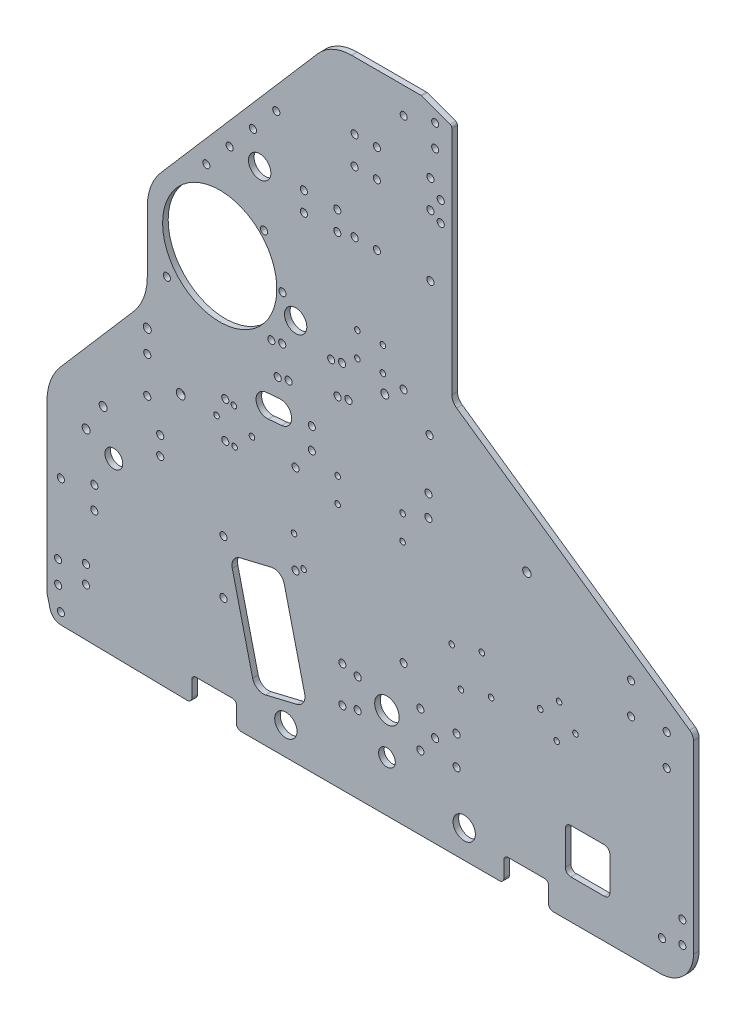
SolidWorks part; units mm, degrees
ref_plane "Front Plane" through (0, 0, 0) normal (0, 0, 1) x (1, 0, 0)
ref_plane "Top Plane" through (0, 0, 0) normal (0, 1, 0) x (1, 0, 0)
ref_plane "Right Plane" through (0, 0, 0) normal (1, 0, 0) x (0, 0, -1)
sketch "Sketch1" plane through (0, 0, 0) normal (0, 0, 1) x (1, 0, 0)
  line L0 (82.55, -20.32) -> (82.55, -6.35)
  line L2 (0, 0) -> (0, 157.48)
  line L4 (368.3, -20.32) -> (368.3, 106.68)
  line L5 (82.55, -6.35) -> (107.95, -6.35)
  line L6 (107.95, -6.35) -> (107.95, -20.32)
  line L7 (107.95, -20.32) -> (260.35, -20.32)
  line L8 (260.35, -20.32) -> (260.35, -6.35)
  line L9 (260.35, -6.35) -> (285.75, -6.35)
  line L10 (285.75, -6.35) -> (285.75, -20.32)
  line L11 (285.75, -20.32) -> (368.3, -20.32)
  line L12 (361.95, 12.7) -> (368.3, 12.7) construction
  line L13 (0, 0) -> (6.35, 0) construction
  line L14 (0.1896, -7.8901) -> (1.7771, -14.2401)
  line L15 (7.8295, -19.0491) -> (82.55, -20.32)
  line L16 (0, 0) -> (0, -6.35)
  line L17 (76.2, 128.905) -> (79.375, 128.905) construction
  line L18 (57.15, 118.5863) -> (101.6, 118.5862) construction
  line L19 (57.15, 118.5863) -> (57.15, 139.2238) construction
  line L20 (101.6, 118.5862) -> (101.6, 139.2237) construction
  line L21 (57.15, 139.2238) -> (101.6, 139.2237) construction
  line L22 (57.15, 118.5863) -> (101.6, 139.2237) construction
  line L23 (101.6, 118.5862) -> (57.15, 139.2238) construction
  line L24 (101.6, 139.2237) -> (125.4682, 147.9111) construction
  line L25 (203.2, 59.805) -> (203.2, 194.805) construction
  line L26 (203.2, 194.805) -> (203.2, 329.805) construction
  line L27 (355.6, 332.105) -> (330.2, 332.105) construction
  line L28 (330.2, 332.105) -> (330.2, 217.805) construction
  line L29 (330.2, 217.805) -> (355.6, 217.805) construction
  line L30 (355.6, 217.805) -> (355.6, 332.105) construction
  line L31 (203.2, 344.805) -> (203.2, 194.805) construction
  line L32 (50.8, 332.105) -> (76.2, 332.105) construction
  line L33 (76.2, 332.105) -> (76.2, 217.805) construction
  line L34 (50.8, 217.805) -> (50.8, 332.105) construction
  line L35 (76.2, 217.805) -> (50.8, 217.805) construction
  line L36 (213.2, 344.805) -> (230.6638, 338.455)
  line L37 (203.2, 344.805) -> (161.925, 344.805)
  line L38 (203.2, 344.805) -> (213.2, 344.805)
  line L39 (348.5362, 344.805) -> (413.4623, 344.805)
  line L40 (348.5362, 344.805) -> (230.6638, 344.805) construction
  line L42 (161.925, 344.805) -> (0, 157.48)
  line L44 (230.6638, 338.455) -> (230.6638, 202.565)
  line L45 (230.6638, 202.565) -> (368.3, 106.68)
  line L46 (213.2, 344.805) -> (-141.0713, 344.805) construction
  line L47 (350.3395, -2.3595) -> (368.3, -20.32) construction
  line L48 (125.4682, 147.9111) -> (133.0592, 148.5752) construction
  line L49 (124.9148, 154.2369) -> (132.5058, 154.901)
  line L50 (126.0216, 141.5852) -> (133.6126, 142.2494)
  circle A0 centre (6.35, 0) radius 2.032
  circle A1 centre (6.35, 12.7) radius 2.032
  circle A2 centre (361.95, 0) radius 2.032
  circle A3 centre (361.95, 12.7) radius 2.032
  arc A5 (1.7771, -14.2401) -> (7.8295, -19.0491) centre (7.9375, -12.7) ccw
  circle A6 centre (7.9375, -12.7) radius 2.032
  arc A7 (0, -6.35) -> (0.1896, -7.8901) centre (6.35, -6.35) ccw
  circle A8 centre (38.1, 78.105) radius 5.08
  circle A9 centre (76.2, 128.905) radius 2.54
  circle A10 centre (101.6, 118.5862) radius 2.032
  circle A11 centre (101.6, 139.2237) radius 2.032
  circle A12 centre (57.15, 139.2238) radius 2.032
  circle A13 centre (57.15, 118.5863) radius 2.032
  circle A15 centre (203.2, 59.805) radius 2
  circle A16 centre (203.2, 194.805) radius 2
  circle A17 centre (203.2, 329.805) radius 2
  circle A18 centre (63.5, 313.055) radius 2.032
  circle A20 centre (355.6, 332.105) radius 2.032
  circle A21 centre (330.2, 332.105) radius 2.032
  circle A22 centre (355.6, 217.805) radius 2.032
  circle A23 centre (330.2, 217.805) radius 2.032
  circle A24 centre (50.8, 332.105) radius 2.032
  circle A25 centre (76.2, 332.105) radius 2.032
  circle A26 centre (50.8, 217.805) radius 2.032
  circle A27 centre (76.2, 217.805) radius 2.032
  circle A28 centre (221.1381, 335.28) radius 2
  circle A29 centre (224.3138, 298.831) radius 2.032
  circle A30 centre (353.06, 100.7351) radius 2.032
  circle A31 centre (332.74, 115.9751) radius 2.032
  circle A32 centre (332.74, 98.1951) radius 2.032
  circle A33 centre (353.06, 82.9551) radius 2.032
  circle A34 centre (117.3562, 280.4276) radius 2.032
  circle A35 centre (104.0678, 265.0548) radius 2.032
  circle A36 centre (90.7795, 249.682) radius 2.032
  circle A38 centre (130.6445, 295.8004) radius 2.032
  circle A39 centre (68.326, 182.9237) radius 2.032
  circle A40 centre (224.3138, 287.401) radius 2.032
  circle A41 centre (125.4682, 147.9111) radius 6.35
  circle A42 centre (221.1381, 322.58) radius 2
  circle A43 centre (350.3395, -2.3595) radius 2.032
  arc A44 (124.9148, 154.2369) -> (126.0216, 141.5852) centre (125.4682, 147.9111) ccw
  arc A45 (133.6126, 142.2494) -> (132.5058, 154.901) centre (133.0592, 148.5752) ccw
  point P82 (203.2, 344.805)
  point P90 (368.3, 62.484)
  point P107 (129.2637, 148.2431)
  dimension "D6" = 4.064
  dimension "D10" = 6.35
  dimension "D11" = 4.064
  dimension "D17" = 38.1
  dimension "D27" = 4
  dimension "D31" = 4.064
  dimension "D32" = 41.275
  dimension "D36" = 4.064
  dimension "D47" = 39.624
  dimension "D48" = 4.064
  dimension "D25" = 5.08
  dimension "D26" = 4.064
  dimension "D52" = 4.064
  dimension "D65" = 4.064
  dimension "D69" = 10.16
  dimension "D72" = 12.7
  dimension "D77" = 6.35
  dimension "D2" = 127
  dimension "D3" = 13.97
  dimension "D4" = 25.4
  dimension "D5" = 152.4
  dimension "D7" = 12.7
  dimension "D8" = 6.35
  dimension "D9" = 20.32
  dimension "D12" = 12.7
  dimension "D13" = 1.5875
  dimension "D14" = 82.55
  dimension "D15" = 368.3
  dimension "D16" = 6.35
  dimension "D18" = 98.425
  dimension "D19" = 38.1
  dimension "D20" = 50.8
  dimension "D21" = 3.175
  dimension "D22" = 270
  dimension "D23" = 20.6375
  dimension "D24" = 44.45
  dimension "D28" = 135
  dimension "D29" = 12.7
  dimension "D30" = 15
  dimension "D33" = 63.5
  dimension "D34" = 27.4638
  dimension "D35" = 12.7
  dimension "D37" = 114.3
  dimension "D38" = 25.4
  dimension "D39" = 12.7
  dimension "D40" = 157.48
  dimension "D41" = 142.24
  dimension "D42" = 365.125
  dimension "D43" = 10
  dimension "D44" = 6.35
  dimension "D45" = 31.75
  dimension "D46" = 3.175
  dimension "D49" = 6.35
  dimension "D50" = 203.2
  dimension "D51" = 15.24
  dimension "D53" = 17.78
  dimension "D54" = 17.78
  dimension "D55" = 20.32
  dimension "D56" = 15.24
  dimension "D57" = 92.202
  dimension "D58" = 8.382
  dimension "D59" = 20.32
  dimension "D60" = 20.32
  dimension "D61" = 8.382
  dimension "D62" = 20.32
  dimension "D63" = 8.382
  dimension "D64" = 8.382
  dimension "D66" = 35.052
  dimension "D67" = 68.326
  dimension "D68" = 11.43
  dimension "D70" = 25.4
  dimension "D71" = 110
  dimension "D73" = 17.9381
  dimension "D74" = 12.7
  dimension "D75" = 45
  dimension "D76" = 25.4
  dimension "D78" = 165
  dimension "D79" = 7.62
extrude "Boss-Extrude1" add sketch "Sketch1" along normal blind 3.175
fillet "Fillet1" radius 2.286 4 edges at (285.75, -6.35, 1.5875) (107.95, -6.35, 1.5875) (260.35, -6.35, 1.5875) (82.55, -6.35, 1.5875)
fillet "Fillet2" radius 6.35 1 edges at (230.6638, 202.565, 1.5875)
sketch "Sketch2" plane through (0, 0, 0) normal (0, 0, -1) x (-1, 0, 0)
  circle A0 centre (-100.5528, 71.086) radius 2.032 construction
  circle A1 centre (-100.5528, 40.606) radius 2.032 construction
  circle A2 centre (-22.225, 18.2025) radius 2.032 construction
  circle A3 centre (-22.225, 8.0425) radius 2.032 construction
  circle A4 centre (-100.5528, 71.086) radius 2.032
  circle A5 centre (-100.5528, 40.606) radius 2.032
  circle A6 centre (-22.225, 18.2025) radius 2.032
  circle A7 centre (-22.225, 8.0425) radius 2.032
extrude "Cut-Extrude1" cut sketch "Sketch2" against normal through all
fillet "Fillet3" radius 1.5875 2 edges at (230.6638, 338.455, 1.5875) (213.2, 344.805, 1.5875)
sketch "Sketch3" plane through (0, 0, 3.175) normal (0, 0, 1) x (1, 0, 0)
  line L0 (132.9524, 63.2646) -> (132.7215, 64.2281) construction
  line L1 (128.3814, 66.8897) -> (110.6828, 62.6472) construction
  line L2 (114.5132, 58.4237) -> (126.8822, 61.3887) construction
  line L3 (108.0212, 58.3071) -> (108.2522, 57.3436) construction
  line L4 (131.2006, 57.703) -> (140.0164, 20.9265) construction
  line L5 (144.0993, 16.7636) -> (132.9524, 63.2646) construction
  line L6 (108.2522, 57.3436) -> (119.3991, 10.8426) construction
  line L7 (121.1509, 16.4042) -> (112.3351, 53.1807) construction
  line L8 (119.3991, 10.8426) -> (119.6301, 9.8791) construction
  line L9 (144.3303, 15.8001) -> (144.0993, 16.7636) construction
  line L10 (137.8383, 15.6835) -> (125.4694, 12.7185) construction
  line L11 (123.9701, 7.2175) -> (141.6687, 11.4601) construction
  line L12 (132.9524, 63.2646) -> (132.7215, 64.2281)
  line L13 (128.3814, 66.8897) -> (110.6828, 62.6472)
  line L14 (114.5132, 58.4237) -> (126.8822, 61.3887)
  line L15 (108.0212, 58.3071) -> (108.2522, 57.3436)
  line L16 (131.2006, 57.703) -> (140.0164, 20.9265)
  line L17 (144.0993, 16.7636) -> (132.9524, 63.2646)
  line L18 (108.2522, 57.3436) -> (119.3991, 10.8426)
  line L19 (121.1509, 16.4042) -> (112.3351, 53.1807)
  line L20 (119.3991, 10.8426) -> (119.6301, 9.8791)
  line L21 (144.3303, 15.8001) -> (144.0993, 16.7636)
  line L22 (137.8383, 15.6835) -> (125.4694, 12.7185)
  line L23 (123.9701, 7.2175) -> (141.6687, 11.4601)
  line L24 (127.7894, 69.3598) -> (110.0908, 65.1172)
  line L25 (105.5512, 57.715) -> (105.7822, 56.7515)
  line L26 (105.7822, 56.7515) -> (116.9291, 10.2505)
  line L27 (116.9291, 10.2505) -> (117.16, 9.287)
  line L28 (124.5622, 4.7475) -> (142.2608, 8.99)
  line L29 (146.8003, 16.3922) -> (146.5694, 17.3557)
  line L30 (146.5694, 17.3557) -> (135.4225, 63.8567)
  line L31 (135.4225, 63.8567) -> (135.1915, 64.8202)
  line L32 (14.605, -0.1369) -> (103.7278, 32.3011) construction
  line L33 (14.605, -0.1369) -> (103.7278, 32.3011)
  line L34 (0, -6.35) -> (0, 157.48) construction
  line L35 (-39.6666, 74.7152) -> (103.7278, 126.9065) construction
  line L36 (26.9875, 46.9531) -> (26.9875, 59.6531) construction
  line L37 (107.95, -20.32) -> (260.35, -20.32) construction
  line L38 (64.5259, 92.5258) -> (64.5259, 102.9405) construction
  line L39 (131.6538, 14.201) -> (136.0946, -4.3242) construction
  line L40 (136.0946, -4.3242) -> (237.6946, -4.3242) construction
  arc A0 (132.7215, 64.2281) -> (128.6308, 66.9403) centre (129.2206, 63.3889) ccw construction
  arc A1 (110.6828, 62.6472) -> (110.4377, 62.5791) centre (111.522, 59.1463) ccw construction
  arc A2 (128.6308, 66.9403) -> (128.3814, 66.8897) centre (129.2206, 63.3889) ccw construction
  arc A3 (110.4377, 62.5791) -> (108.0212, 58.3071) centre (111.522, 59.1463) ccw construction
  arc A4 (119.6301, 9.8791) -> (123.7207, 7.1669) centre (123.1309, 10.7183) ccw construction
  arc A5 (141.9139, 11.5281) -> (144.3303, 15.8001) centre (140.8295, 14.9609) ccw construction
  arc A6 (141.6687, 11.4601) -> (141.9139, 11.5281) centre (140.8295, 14.9609) ccw construction
  arc A7 (123.7207, 7.1669) -> (123.9701, 7.2175) centre (123.1309, 10.7183) ccw construction
  arc A8 (132.7215, 64.2281) -> (128.6308, 66.9403) centre (129.2206, 63.3889) ccw
  arc A9 (110.6828, 62.6472) -> (110.4377, 62.5791) centre (111.522, 59.1463) ccw
  arc A10 (128.6308, 66.9403) -> (128.3814, 66.8897) centre (129.2206, 63.3889) ccw
  arc A11 (110.4377, 62.5791) -> (108.0212, 58.3071) centre (111.522, 59.1463) ccw
  arc A12 (119.6301, 9.8791) -> (123.7207, 7.1669) centre (123.1309, 10.7183) ccw
  arc A13 (141.9139, 11.5281) -> (144.3303, 15.8001) centre (140.8295, 14.9609) ccw
  arc A14 (141.6687, 11.4601) -> (141.9139, 11.5281) centre (140.8295, 14.9609) ccw
  arc A15 (123.7207, 7.1669) -> (123.9701, 7.2175) centre (123.1309, 10.7183) ccw
  arc A16 (110.0908, 65.1172) -> (109.6726, 65.0012) centre (111.522, 59.1463) ccw
  arc A17 (109.6726, 65.0012) -> (105.5512, 57.715) centre (111.522, 59.1463) ccw
  arc A18 (117.16, 9.287) -> (124.1369, 4.6613) centre (123.1309, 10.7183) ccw
  arc A19 (124.1369, 4.6613) -> (124.5622, 4.7475) centre (123.1309, 10.7183) ccw
  arc A20 (142.2608, 8.99) -> (142.6789, 9.1061) centre (140.8295, 14.9609) ccw
  arc A21 (142.6789, 9.1061) -> (146.8003, 16.3922) centre (140.8295, 14.9609) ccw
  arc A22 (135.1915, 64.8202) -> (128.2147, 69.446) centre (129.2206, 63.3889) ccw
  arc A23 (128.2147, 69.446) -> (127.7894, 69.3598) centre (129.2206, 63.3889) ccw
  circle A24 centre (136.0946, -4.3242) radius 6.35
  circle A25 centre (237.6946, -4.3242) radius 6.35
  circle A26 centre (134.1438, 208.2281) radius 2.032 construction
  circle A33 centre (26.9875, 46.9531) radius 2.032
  circle A34 centre (26.9875, 59.6531) radius 2.032
  circle A35 centre (7.9375, 53.3031) radius 2.032
  circle A37 centre (32.0306, 100.8109) radius 32.385 construction
  circle A38 centre (32.0306, 100.8109) radius 2.286
  circle A39 centre (123.682, 233.4851) radius 2.032 construction
  circle A40 centre (64.5259, 102.9405) radius 2.032
  circle A41 centre (64.5259, 92.5258) radius 2.032
  circle A42 centre (134.1438, 208.2281) radius 2.032
  circle A43 centre (123.682, 233.4851) radius 2.032
  ellipse E0 centre (124.5974, 48.8487) end of major axis (128.5376, 61.3578) minor radius 6 (131.2006, 57.703) -> (126.8822, 61.3887) ccw construction
  ellipse E1 centre (122.2349, 48.2824) end of major axis (113.0518, 57.6456) minor radius 6 (114.5132, 58.4237) -> (112.3351, 53.1807) ccw construction
  ellipse E2 centre (127.7541, 25.2585) end of major axis (131.6942, 37.7675) minor radius 6 (121.1509, 16.4042) -> (125.4694, 12.7185) ccw construction
  ellipse E3 centre (130.1166, 25.8248) end of major axis (139.2998, 16.4616) minor radius 6 (137.8383, 15.6835) -> (140.0164, 20.9265) ccw construction
  ellipse E4 centre (124.5974, 48.8487) end of major axis (120.6573, 36.3397) minor radius 6 (131.2006, 57.703) -> (126.8822, 61.3887) ccw
  ellipse E5 centre (122.2349, 48.2824) end of major axis (131.4181, 38.9192) minor radius 6 (114.5132, 58.4237) -> (112.3351, 53.1807) ccw
  ellipse E6 centre (127.7541, 25.2585) end of major axis (131.6942, 37.7675) minor radius 6 (121.1509, 16.4042) -> (125.4694, 12.7185) ccw
  ellipse E7 centre (130.1166, 25.8248) end of major axis (139.2998, 16.4616) minor radius 6 (137.8383, 15.6835) -> (140.0164, 20.9265) ccw
  point P93 (26.9875, 53.3031)
  point P115 (32.0306, 100.8109)
  dimension "D3" = 64.77
  dimension "D4" = 4.572
  dimension "D8" = 4.064
  dimension "D13" = 12.7
  dimension "D15" = 101.6
  dimension "D2" = 88.9
  dimension "D5" = 7.9375
  dimension "D6" = 19.05
  dimension "D7" = 73.6231
  dimension "D9" = 12.7
  dimension "D10" = 10.4147
  dimension "D11" = 37.5384
  dimension "D12" = 45.5727
  dimension "D14" = 19.05
  dimension "D1" = 2.54
extrude "Cut-Extrude2" cut sketch "Sketch3" against normal through all contours A22 A23 L24 A16 A17 L25 L26 L27 A18 A19 L28 A20 A21 L29 L30 L31 A15 A12 L20 L18 L15 A11 A9 L13 A10 A8 L12 L17 L21 A13 A14 L23 | A12 A15 L23 A14 A13 L21 L17 L12 A8 A10 L13 A9 A11 L15 L18 L20 E7 L22 E6 L19 E5 L14 E4 L16 | L22 E7 L16 E4 L14 E5 L19 E6 | A38 | A41 | A40 | A35 | A34 | A33 | A43 | A42 | A24 | A25
sketch "Sketch4" plane through (0, 0, 3.175) normal (0, 0, 1) x (1, 0, 0)
  line L0 (57.15, 139.2238) -> (101.6, 139.2237) construction
  line L1 (168.275, 21.4312) -> (212.725, 21.4312) construction
  line L2 (168.275, 21.4312) -> (168.275, 42.0687) construction
  line L3 (168.275, 42.0687) -> (212.725, 42.0687) construction
  line L4 (212.725, 21.4312) -> (212.725, 42.0687) construction
  line L5 (168.275, 21.4312) -> (212.725, 42.0687) construction
  line L6 (168.275, 42.0687) -> (212.725, 21.4312) construction
  line L7 (57.15, 118.5863) -> (57.15, 139.2238) construction
  line L8 (107.95, -20.32) -> (260.35, -20.32) construction
  line L9 (193.675, 31.75) -> (177.005, 31.75) construction
  line L10 (190.5, 31.75) -> (193.675, 31.75) construction
  line L11 (6.35, 12.7) -> (361.95, 12.7) construction
  line L12 (107.95, -6.35) -> (107.95, -20.32) construction
  line L13 (193.675, 31.75) -> (220.6625, 31.75) construction
  line L14 (177.005, 23.4569) -> (177.005, 40.0431) construction
  line L15 (213.2, 44.805) -> (193.2, 44.805) construction
  line L16 (213.2, 44.805) -> (213.2, 344.805) construction
  line L17 (213.2, 344.805) -> (193.2, 344.805) construction
  line L18 (193.2, 44.805) -> (193.2, 344.805) construction
  line L19 (213.2, 44.805) -> (193.2, 344.805) construction
  line L20 (213.2, 344.805) -> (193.2, 44.805) construction
  line L21 (226.1381, 335.28) -> (226.1381, 31.75) construction
  line L22 (237.33, 40.0431) -> (233.3612, 40.0431) construction
  line L23 (237.33, 23.4569) -> (233.3612, 23.4569) construction
  circle A0 centre (168.275, 42.0687) radius 2.032
  circle A1 centre (212.725, 42.0687) radius 2.032
  circle A2 centre (212.725, 21.4312) radius 2.032
  circle A3 centre (168.275, 21.4312) radius 2.032
  circle A4 centre (193.675, 31.75) radius 6.985
  circle A7 centre (220.6625, 31.75) radius 14.2875 construction
  circle A8 centre (193.675, 31.75) radius 12.7 construction
  circle A9 centre (177.005, 40.0431) radius 2.032
  circle A10 centre (177.005, 23.4569) radius 2.032
  circle A11 centre (237.33, 40.0431) radius 2.032 construction
  circle A12 centre (237.33, 23.4569) radius 2.032 construction
  circle A13 centre (193.675, 8.4667) radius 4.7625
  circle A14 centre (221.1381, 31.75) radius 2.032
  circle A15 centre (221.1381, 31.75) radius 5 construction
  circle A16 centre (221.1381, 335.28) radius 5 construction
  circle A17 centre (233.3612, 23.4569) radius 2.032
  circle A18 centre (233.3612, 40.0431) radius 2.032
  point P0 (190.5, 31.75)
  point P26 (203.2, 194.805)
  point P38 (177.005, 31.75)
  dimension "D1" = 4.064
  dimension "D4" = 13.97
  dimension "D7" = 9.525
  dimension "D10" = 25.4
  dimension "D11" = 28.575
  dimension "D16" = 10
  dimension "D17" = 4.064
  dimension "D18" = 10
  dimension "D2" = 52.07
  dimension "D3" = 3.175
  dimension "D5" = 82.55
  dimension "D6" = 26.9875
  dimension "D8" = 20
  dimension "D9" = 300
  dimension "D12" = 16.67
  dimension "D13" = 16.5862
  dimension "D14" = 60.325
  dimension "D15" = 23.2833
  dimension "D19" = 3.9688
extrude "Cut-Extrude3" cut sketch "Sketch4" against normal through all
sketch "Sketch5" plane through (0, 0, 0) normal (0, 0, -1) x (-1, 0, 0)
  line L0 (-57.15, 223.5947) -> (-57.15, 165.3337)
  line L1 (-161.925, 344.805) -> (-52.7201, 218.4699) construction
  line L2 (-57.15, 165.3337) -> (0, 99.219)
  line L3 (0, -6.35) -> (0, 157.48) construction
  line L4 (-147.864, -30.311) -> (-147.864, -16.0874)
  line L5 (-50.4199, 215.8089) -> (0, 157.48) construction
  line L6 (-57.15, 223.5947) -> (0, 157.48)
  line L7 (0, 157.48) -> (0, 99.219)
  line L8 (-98.425, 208.2281) -> (-141.6756, 197.9719) construction
  line L9 (-368.3, -20.32) -> (-368.3, 106.68) construction
  line L10 (-285.75, -20.32) -> (-368.3, -20.32) construction
  circle A0 centre (-98.425, 208.2281) radius 32.5437
  circle A1 centre (-141.6756, 197.9719) radius 6.35
  circle A3 centre (-273.4056, 139.7279) radius 2.39
  dimension "D3" = 65.0875
  dimension "D7" = 12.7
  dimension "D8" = 4.78
  dimension "D1" = 38.1
  dimension "D2" = 57.15
  dimension "D4" = 41.275
  dimension "D5" = 41.275
  dimension "D6" = 94.8944
  dimension "D9" = 22.2382
  dimension "D10" = 160.0479
  dimension "D11" = 11.6447
  dimension "D14" = 62.5
  dimension "D13" = 44.45
extrude "Cut-Extrude5" cut sketch "Sketch5" against normal through all contours A0 | L7 L6 L0 L2 | A3
fillet "Fillet4" radius 31.75 3 edges at (0, 99.219, 1.5875) (57.15, 165.3337, 1.5875) (57.15, 223.5947, 1.5875)
sketch "Sketch6" plane through (0, 0, 3.175) normal (0, 0, 1) x (1, 0, 0)
  line L0 (285.75, -20.32) -> (368.3, -20.32) construction
  line L1 (298.45, 27.305) -> (317.5, 27.305)
  line L2 (295.275, 24.13) -> (295.275, 5.08)
  line L3 (298.45, 1.905) -> (317.5, 1.905)
  line L4 (320.675, 24.13) -> (320.675, 5.08)
  line L5 (295.275, 27.305) -> (320.675, 1.905) construction
  line L6 (295.275, 1.905) -> (320.675, 27.305) construction
  line L7 (368.3, -20.32) -> (368.3, 106.68) construction
  arc A0 (295.275, 5.08) -> (298.45, 1.905) centre (298.45, 5.08) ccw
  arc A1 (317.5, 1.905) -> (320.675, 5.08) centre (317.5, 5.08) ccw
  arc A2 (317.5, 27.305) -> (320.675, 24.13) centre (317.5, 24.13) cw
  arc A3 (298.45, 27.305) -> (295.275, 24.13) centre (298.45, 24.13) ccw
  point P0 (307.975, 14.605)
  dimension "D2" = 3.175
  dimension "D1" = 25.4
  dimension "D3" = 22.225
  dimension "D4" = 47.625
extrude "Cut-Extrude6" cut sketch "Sketch6" against normal through all
fillet "Fillet5" radius 25.4 1 edges at (161.925, 344.805, 1.5875)
sketch "Sketch8" plane through (0, 0, 0) normal (0, 0, -1) x (-1, 0, 0)
  line L0 (-230.6638, 337.343) -> (-230.6638, 205.8802) construction
  line L1 (-230.6638, 255.905) -> (-175.26, 255.905) construction
  line L2 (-175.26, 255.905) -> (-175.26, 306.705) construction
  line L3 (-175.26, 306.705) -> (-230.6638, 306.705) construction
  line L4 (-173.5432, 344.805) -> (-212.9203, 344.805) construction
  line L7 (-107.95, -20.32) -> (-260.35, -20.32) construction
  circle A0 centre (-218.44, 290.83) radius 3.9687
  circle A1 centre (-218.44, 290.83) radius 2.032
  circle A2 centre (218.44, 265.7972) radius 3.9687
  circle A3 centre (218.44, 265.7972) radius 2.032
  circle A4 centre (-205.74, 290.83) radius 3.9687
  circle A5 centre (-205.74, 290.83) radius 2.032
  circle A6 centre (-187.96, 290.83) radius 3.9687
  circle A7 centre (-187.96, 290.83) radius 2.032
  circle A8 centre (-187.96, 306.705) radius 2.032
  circle A9 centre (-175.26, 290.83) radius 3.9687
  circle A10 centre (-175.26, 290.83) radius 2.032
  circle A11 centre (-205.74, 306.705) radius 2.032
  circle A13 centre (-205.74, 255.905) radius 2.032
  circle A14 centre (-187.96, 255.905) radius 2.032
  circle A16 centre (-218.44, 306.705) radius 2.032
  circle A17 centre (-175.26, 306.705) radius 2.032
  circle A18 centre (-175.26, 255.905) radius 2.032
  circle A19 centre (-218.44, 255.905) radius 2.032
  circle A20 centre (-218.44, 306.705) radius 3.9687
  circle A21 centre (-205.74, 306.705) radius 3.9687
  circle A22 centre (-175.26, 306.705) radius 3.9687
  circle A23 centre (-218.44, 255.905) radius 3.9687
  circle A24 centre (-205.74, 255.905) radius 3.9687
  circle A25 centre (-187.96, 255.905) radius 3.9687
  circle A26 centre (-175.26, 255.905) radius 3.9687
  circle A27 centre (-187.96, 306.705) radius 3.9687
  dimension "D1" = 7.9375
  dimension "D7" = 4.064
  dimension "D13" = 12.2237
  dimension "D2" = 12.2237
  dimension "D3" = 12.7
  dimension "D4" = 17.78
  dimension "D5" = 12.7
  dimension "D6" = 88.9
  dimension "D8" = 38.1
  dimension "D9" = 17.78
  dimension "D10" = 12.7
  dimension "D11" = 55.4037
  dimension "D12" = 12.7
  dimension "D14" = 311.15
extrude "Cut-Extrude7" cut sketch "Sketch8" against normal through all
sketch "Sketch10" plane through (0, 0, 3.175) normal (0, 0, 1) x (1, 0, 0)
  circle A4 centre (141.6425, 74.6844) radius 2.032 construction
  circle A5 centre (141.6425, 125.4844) radius 2.032 construction
  circle A6 centre (141.6425, 74.6844) radius 2.032
  circle A7 centre (141.6425, 125.4844) radius 2.032
extrude "Cut-Extrude8" cut sketch "Sketch10" against normal through all
sketch "Sketch11" plane through (0, 0, 3.175) normal (0, 0, 1) x (1, 0, 0)
  ellipse E4 centre (150.8814, 138.43) end of major axis (150.8814, 140.462) minor radius 2.032
  ellipse E5 centre (150.8814, 150.495) end of major axis (150.8814, 152.527) minor radius 2.032
  ellipse E6 centre (217.3024, 150.495) end of major axis (217.3024, 152.527) minor radius 2.032
  ellipse E7 centre (217.3024, 138.43) end of major axis (217.3024, 140.462) minor radius 2.032
extrude "Cut-Extrude9" cut sketch "Sketch11" against normal through all
sketch "Sketch12" plane through (0, 0, 0) normal (0, 0, -1) x (-1, 0, 0)
  line L0 (-173.5432, 344.805) -> (-212.9203, 344.805) construction
  circle A0 centre (-165.4175, 264.635) radius 2.032
  circle A1 centre (-203.2, 329.805) radius 2 construction
  circle A2 centre (-165.4175, 253.5225) radius 2.032
  circle A3 centre (-146.3675, 253.5225) radius 2.032
  circle A4 centre (-146.3675, 264.635) radius 2.032
  dimension "D1" = 80.17
  dimension "D2" = 4.064
  dimension "D3" = 37.7825
  dimension "D4" = 11.1125
  dimension "D5" = 19.05
extrude "Cut-Extrude10" cut sketch "Sketch12" against normal through all
sketch "Sketch14" plane through (0, 0, 0) normal (0, 0, -1) x (-1, 0, 0)
  line L0 (-130.6445, 295.8004) -> (-121.1847, 263.6885) construction
  line L1 (-121.1847, 263.6885) -> (-90.7795, 249.682) construction
  line L2 (-154.3272, 336.0154) -> (-64.88, 232.5373) construction
  line L4 (-118.517, 269.4796) -> (-115.3937, 261.0208) construction
  line L5 (-118.517, 269.4796) -> (-126.9758, 266.3562) construction
  line L6 (-126.9758, 266.3562) -> (-123.8524, 257.8974) construction
  line L7 (-115.3937, 261.0208) -> (-123.8524, 257.8974) construction
  line L8 (-118.517, 269.4796) -> (-123.8524, 257.8974) construction
  line L9 (-126.9758, 266.3562) -> (-115.3937, 261.0208) construction
  circle A0 centre (-121.1847, 263.6885) radius 6.376
  dimension "D1" = 22.225
  dimension "D2" = 9.017
extrude "Cut-Extrude11" cut sketch "Sketch14" against normal through all
sketch "Sketch15" plane through (0, 0, 3.175) normal (0, 0, 1) x (1, 0, 0)
  line L0 (38.1, 78.105) -> (35.0376, 98.2034) construction
  line L1 (20.5874, 75.6997) -> (81.7263, 75.6997) construction
  line L2 (57.15, 139.2238) -> (57.15, 151.9238) construction
  line L3 (52.4937, 153.9549) -> (22.3594, 84.8727) construction
  line L4 (56.0505, 156.8833) -> (192.439, 187.1199) construction
  line L5 (52.4937, 153.9549) -> (37.8292, 107.1192) construction
  line L6 (20.5874, 75.6997) -> (38.1, 78.105) construction
  line L7 (35.0376, 98.2034) -> (37.8292, 107.1192) construction
  line L8 (20.5874, 75.6997) -> (22.3594, 84.8727) construction
  line L9 (38.1, 78.105) -> (17.7697, 78.105) construction
  line L10 (17.7697, 78.105) -> (21.6585, 86.5998) construction
  line L11 (21.6585, 86.5998) -> (52.4937, 153.9549) construction
  circle A0 centre (20.5874, 75.6997) radius 2.159 construction
  circle A1 centre (20.5874, 75.6997) radius 2.159 construction
  circle A2 centre (57.15, 139.2238) radius 2.032 construction
  circle A3 centre (57.15, 139.2238) radius 2.032 construction
  circle A4 centre (57.15, 151.9238) radius 2.286
  circle A5 centre (192.439, 187.1199) radius 2.286
  circle A6 centre (57.15, 151.9238) radius 5.08 construction
  circle A7 centre (38.1, 78.105) radius 2.159 construction
  circle A8 centre (38.1, 78.105) radius 2.159
  arc A9 (163.8737, 173.6806) -> (164.5125, 170.7993) centre (165.557, 172.5423) ccw construction
  arc A10 (173.4398, 172.7784) -> (172.801, 175.6597) centre (171.7565, 173.9167) ccw construction
  arc A11 (172.801, 175.6597) -> (173.4398, 172.7784) centre (171.7565, 173.9167) ccw construction
  arc A12 (164.5125, 170.7993) -> (163.8737, 173.6806) centre (165.557, 172.5423) ccw construction
  arc A13 (169.1589, 192.0883) -> (169.7976, 189.2071) centre (168.1143, 190.3453) ccw construction
  arc A14 (169.7976, 189.2071) -> (169.1589, 192.0883) centre (168.1143, 190.3453) ccw construction
  arc A15 (160.2316, 190.1092) -> (160.8704, 187.2279) centre (161.9149, 188.9709) ccw construction
  arc A16 (160.8704, 187.2279) -> (160.2316, 190.1092) centre (161.9149, 188.9709) ccw construction
  arc A17 (129.7766, 166.1214) -> (130.4154, 163.2402) centre (131.4599, 164.9832) ccw construction
  arc A18 (139.3426, 165.2193) -> (138.7039, 168.1005) centre (137.6593, 166.3576) ccw construction
  arc A19 (138.7039, 168.1005) -> (139.3426, 165.2193) centre (137.6593, 166.3576) ccw construction
  arc A20 (130.4154, 163.2402) -> (129.7766, 166.1214) centre (131.4599, 164.9832) ccw construction
  arc A21 (135.7005, 181.6479) -> (135.0617, 184.5292) centre (134.0172, 182.7862) ccw construction
  arc A22 (135.0617, 184.5292) -> (135.7005, 181.6479) centre (134.0172, 182.7862) ccw construction
  arc A23 (126.1345, 182.55) -> (126.7732, 179.6688) centre (127.8177, 181.4118) ccw construction
  arc A24 (126.7732, 179.6688) -> (126.1345, 182.55) centre (127.8177, 181.4118) ccw construction
  arc A25 (163.8737, 173.6806) -> (164.5125, 170.7993) centre (165.557, 172.5423) ccw
  arc A26 (173.4398, 172.7784) -> (172.801, 175.6597) centre (171.7565, 173.9167) ccw
  arc A27 (172.801, 175.6597) -> (173.4398, 172.7784) centre (171.7565, 173.9167) ccw
  arc A28 (164.5125, 170.7993) -> (163.8737, 173.6806) centre (165.557, 172.5423) ccw
  arc A29 (169.1589, 192.0883) -> (169.7976, 189.2071) centre (168.1143, 190.3453) ccw
  arc A30 (169.7976, 189.2071) -> (169.1589, 192.0883) centre (168.1143, 190.3453) ccw
  arc A31 (160.2316, 190.1092) -> (160.8704, 187.2279) centre (161.9149, 188.9709) ccw
  arc A32 (160.8704, 187.2279) -> (160.2316, 190.1092) centre (161.9149, 188.9709) ccw
  arc A33 (129.7766, 166.1214) -> (130.4154, 163.2402) centre (131.4599, 164.9832) ccw
  arc A34 (139.3426, 165.2193) -> (138.7039, 168.1005) centre (137.6593, 166.3576) ccw
  arc A35 (138.7039, 168.1005) -> (139.3426, 165.2193) centre (137.6593, 166.3576) ccw
  arc A36 (130.4154, 163.2402) -> (129.7766, 166.1214) centre (131.4599, 164.9832) ccw
  arc A37 (135.7005, 181.6479) -> (135.0617, 184.5292) centre (134.0172, 182.7862) ccw
  arc A38 (135.0617, 184.5292) -> (135.7005, 181.6479) centre (134.0172, 182.7862) ccw
  arc A39 (126.1345, 182.55) -> (126.7732, 179.6688) centre (127.8177, 181.4118) ccw
  arc A40 (126.7732, 179.6688) -> (126.1345, 182.55) centre (127.8177, 181.4118) ccw
  circle A41 centre (22.3594, 84.8727) radius 2.286 construction
  circle A42 centre (22.3594, 84.8727) radius 2.286
  point P39 (52.4937, 153.9549)
  dimension "D2" = 4.572
  dimension "D6" = 10.16
  dimension "D1" = 12.7
  dimension "D3" = 139.7
  dimension "D4" = 12.5
  dimension "D5" = 74.0778
  dimension "D7" = 49.0778
extrude "Cut-Extrude12" cut sketch "Sketch15" against normal through all
sketch "Sketch16" plane through (0, 0, 3.175) normal (0, 0, 1) x (1, 0, 0)
  circle A0 centre (98.425, 208.2281) radius 34.925 construction
  circle A1 centre (98.425, 208.2281) radius 34.925
  circle A2 centre (98.425, 208.2281) radius 36.195
  dimension "D1" = 1.27
fillet "Fillet7" radius 5.08 1 edges at (368.3, 106.68, 1.5875)
fillet "Fillet8" radius 2.54 4 edges at (82.55, -20.32, 1.5875) (107.95, -20.32, 1.5875) (260.35, -20.32, 1.5875) (285.75, -20.32, 1.5875)
sketch "Sketch17" plane through (0, 0, 3.175) normal (0, 0, 1) x (1, 0, 0)
  line L0 (230.6638, 337.343) -> (230.6638, 205.8802) construction
  line L1 (173.5432, 344.805) -> (212.9203, 344.805) construction
  circle A0 centre (217.9638, 179.705) radius 2.032
  dimension "D1" = 12.7
  dimension "D3" = 4.064
  dimension "D2" = 165.1
extrude "Cut-Extrude13" cut sketch "Sketch17" against normal through all
fillet "Fillet9" radius 19.05 1 edges at (368.3, -20.32, 1.5875)
sketch "Sketch18" plane through (0, 0, 3.175) normal (0, 0, 1) x (1, 0, 0)
  line L0 (150.8814, 138.43) -> (217.3024, 138.43) construction
  line L1 (184.0919, 138.43) -> (184.0919, 119.38) construction
  line L2 (165.5919, 119.38) -> (202.5919, 119.38) construction
  line L3 (184.0919, 138.43) -> (184.0919, 210.82) construction
  line L4 (176.8148, 210.82) -> (191.369, 210.82) construction
  line L5 (184.0919, 138.43) -> (184.0919, 65.405) construction
  line L7 (244.4169, 65.405) -> (184.0919, 65.405) construction
  line L8 (253.004, 67.7059) -> (235.8298, 63.1041) construction
  line L9 (202.5919, 133.35) -> (165.5919, 133.35) construction
  line L10 (230.5706, 82.7317) -> (247.7448, 87.3335) construction
  line L11 (244.4169, 65.405) -> (239.1577, 85.0326) construction
  line L12 (184.0919, 119.38) -> (143.4519, 119.38) construction
  line L13 (143.4519, 119.38) -> (143.4519, 85.09) construction
  line L14 (146.1667, 77.6312) -> (140.7371, 92.5488) construction
  line L15 (184.0919, 138.43) -> (116.7819, 138.43) construction
  line L16 (116.7819, 138.43) -> (116.7819, 128.27) construction
  line L17 (116.7819, 128.27) -> (106.4905, 138.5614) construction
  line L18 (111.6362, 133.4157) -> (101.7579, 123.5374) construction
  line L19 (184.0919, 138.43) -> (285.6919, 138.43) construction
  line L20 (285.6919, 138.43) -> (285.6919, 70.485) construction
  line L21 (290.3695, 64.9104) -> (281.0143, 76.0596) construction
  line L22 (96.6123, 128.6831) -> (106.9036, 118.3917) construction
  line L23 (184.0919, 210.82) -> (184.0919, 196.85) construction
  line L24 (176.8148, 196.85) -> (191.369, 196.85) construction
  line L25 (285.6919, 70.485) -> (296.3936, 79.4647) construction
  line L26 (291.7159, 85.0393) -> (301.0712, 73.8902) construction
  circle A1 centre (150.8814, 138.43) radius 2.032 construction
  circle A2 centre (217.3024, 138.43) radius 2.032 construction
  circle A3 centre (150.8814, 138.43) radius 2.032
  circle A4 centre (217.3024, 138.43) radius 2.032
  circle A5 centre (165.5919, 119.38) radius 1.5875
  circle A6 centre (202.5919, 119.38) radius 1.5875
  circle A7 centre (176.8148, 210.82) radius 1.5875
  circle A8 centre (191.369, 210.82) radius 1.5875
  circle A9 centre (165.5919, 133.35) radius 1.5875
  circle A10 centre (202.5919, 133.35) radius 1.5875
  circle A11 centre (235.8298, 63.1041) radius 1.5875
  circle A12 centre (253.004, 67.7059) radius 1.5875
  circle A13 centre (230.5706, 82.7317) radius 1.5875
  circle A14 centre (247.7448, 87.3335) radius 1.5875
  circle A15 centre (140.7371, 92.5488) radius 1.5875
  circle A16 centre (146.1667, 77.6312) radius 1.5875
  circle A17 centre (116.7819, 128.27) radius 1.5875
  circle A18 centre (106.4905, 138.5614) radius 1.5875
  circle A20 centre (281.0143, 76.0596) radius 1.5875
  circle A21 centre (290.3695, 64.9104) radius 1.5875
  circle A22 centre (96.6123, 128.6831) radius 1.5875
  circle A23 centre (106.9036, 118.3917) radius 1.5875
  circle A24 centre (176.8148, 196.85) radius 1.5875
  circle A25 centre (191.369, 196.85) radius 1.5875
  circle A26 centre (291.7159, 85.0393) radius 1.5875
  circle A27 centre (301.0712, 73.8902) radius 1.5875
  point P3 (184.0919, 119.38)
  point P17 (184.0919, 210.82)
  point P24 (244.4169, 65.405)
  point P27 (184.0919, 133.35)
  point P41 (143.4519, 85.09)
  point P55 (285.6919, 70.485)
  point P60 (101.7579, 123.5374)
  point P66 (184.0919, 196.85)
  point P72 (296.3936, 79.4647)
  dimension "D3" = 3.175
  dimension "D6" = 73.025
  dimension "D8" = 13.97
  dimension "D11" = 20.32
  dimension "D12" = 40.64
  dimension "D14" = 15.875
  dimension "D18" = 45
  dimension "D23" = 14.5542
  dimension "D20" = 13.97
  dimension "D25" = 13.97
  dimension "D26" = 13.97
  dimension "D1" = 19.05
  dimension "D2" = 37
  dimension "D4" = 72.39
  dimension "D5" = 14.5542
  dimension "D7" = 60.325
  dimension "D9" = 17.78
  dimension "D10" = 75
  dimension "D13" = 34.29
  dimension "D15" = 20
  dimension "D16" = 67.31
  dimension "D17" = 10.16
  dimension "D19" = 14.5542
  dimension "D21" = 101.6
  dimension "D22" = 67.945
  dimension "D24" = 40
extrude "Cut-Extrude14" cut sketch "Sketch18" against normal through all
equation "\"D7@Sketch15\"=\"D5@Sketch15\"-25mm"
